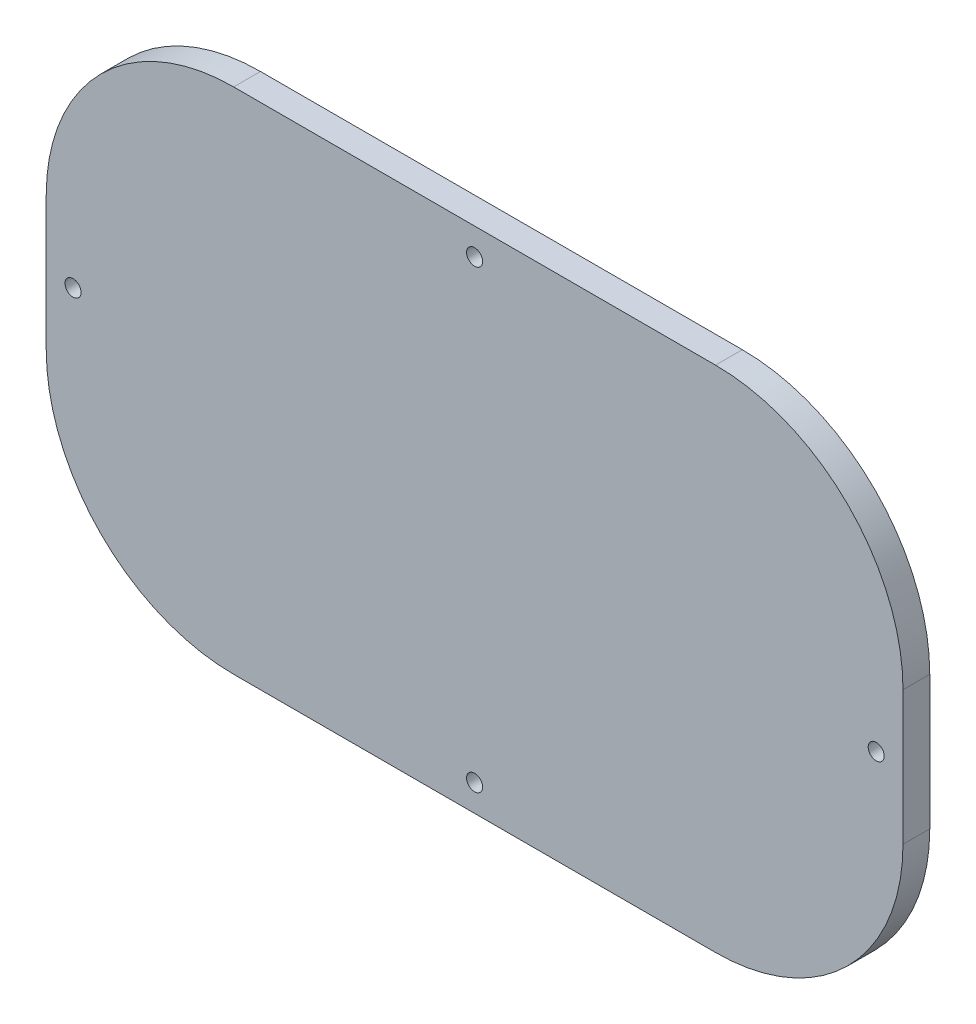
SolidWorks part; units mm, degrees
ref_plane "Plan de face" through (0, 0, 0) normal (0, 0, 1) x (1, 0, 0)
ref_plane "Plan de dessus" through (0, 0, 0) normal (0, 1, 0) x (1, 0, 0)
ref_plane "Plan de droite" through (0, 0, 0) normal (1, 0, 0) x (0, 0, -1)
sketch "Esquisse1" plane through (0, 0, 0) normal (0, 0, 1) x (1, 0, 0)
  line L4 (1.108, 47.0845) -> (1.108, 37.0845) construction
  line L5 (46.108, 47.0845) -> (-43.892, 47.0845)
  line L6 (-78.892, 12.0845) -> (-78.892, -12.9155)
  line L7 (-43.892, -47.9155) -> (46.108, -47.9155)
  line L8 (81.108, -12.9155) -> (81.108, 12.0845)
  line L9 (1.108, -37.9155) -> (1.108, -47.9155) construction
  circle A4 centre (-73.892, -0.4155) radius 1.5
  circle A5 centre (76.108, -0.4155) radius 1.5
  circle A6 centre (1.108, 42.0845) radius 1.5
  circle A7 centre (1.108, -42.9155) radius 1.5
  arc A8 (81.108, 12.0845) -> (46.108, 47.0845) centre (46.108, 12.0845) ccw
  arc A9 (-43.892, 47.0845) -> (-78.892, 12.0845) centre (-43.892, 12.0845) ccw
  arc A10 (-78.892, -12.9155) -> (-43.892, -47.9155) centre (-43.892, -12.9155) ccw
  arc A11 (46.108, -47.9155) -> (81.108, -12.9155) centre (46.108, -12.9155) ccw
extrude "Boss.-Extru.1" add sketch "Esquisse1" along normal blind 5
